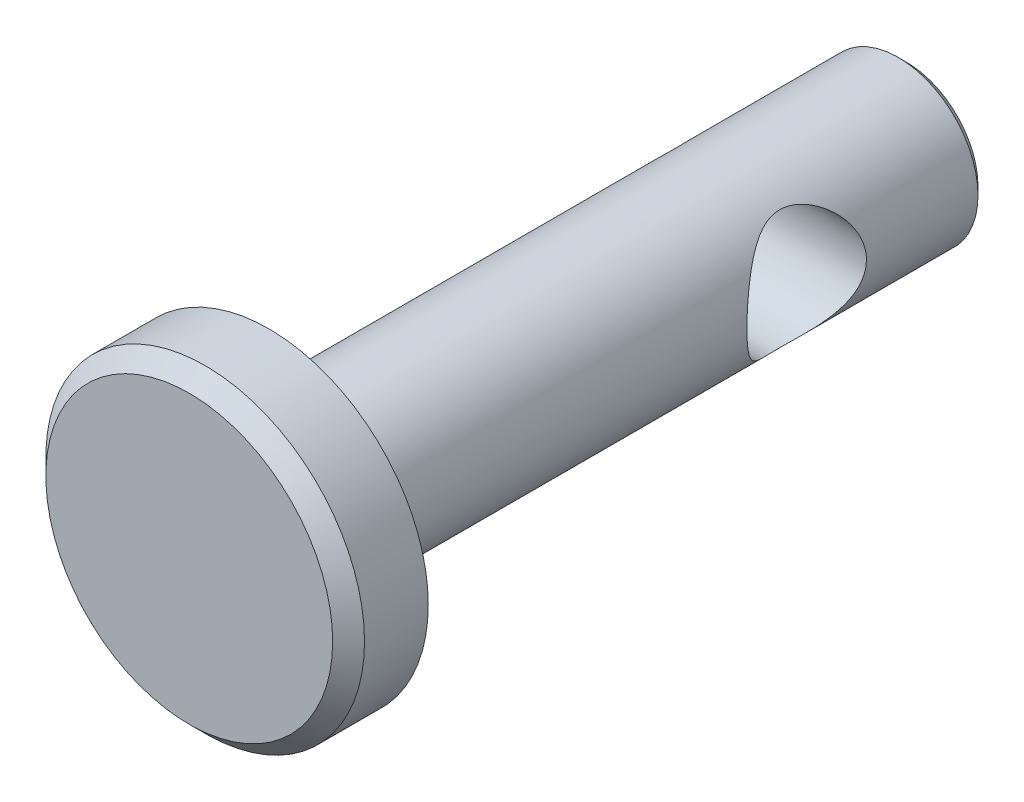
SolidWorks part; units mm, degrees
ref_plane "Front" through (0, 0, 0) normal (0, 0, 1) x (1, 0, 0)
ref_plane "Top" through (0, 0, 0) normal (0, 1, 0) x (1, 0, 0)
ref_plane "Right" through (0, 0, 0) normal (1, 0, 0) x (0, 0, -1)
sketch "Sketch1" plane through (0, 0, 0) normal (0, 0, 1) x (1, 0, 0)
  circle A0 centre (0, 0) radius 1.5875
  point P3 (0, 1.5875)
  point P4 (0, -1.5875)
  dimension "dia" = 3.175
extrude "Extrude1" add sketch "Sketch1" along normal mid plane 12.7
sketch "Sketch2" plane through (0, 0, 6.35) normal (0, 0, 1) x (1, 0, 0)
  circle A0 centre (0, 0) radius 3.175
  dimension "head dia" = 6.35
extrude "Extrude2" add sketch "Sketch2" along normal blind 1.5875
chamfer "Chamfer1" distance 0.3175 angle 45 1 edges at (3.175, 0, 7.9375)
sketch "Sketch3" plane through (0, 0, 0) normal (1, 0, 0) x (0, 0, -1)
  line L0 (-6.35, -1.5875) -> (-6.35, 1.5875) construction
  circle A0 centre (2.7781, 0) radius 1.1906
  point P2 (1.5875, 0)
  dimension "hole dia" = 2.3813
  dimension "useable Lg" = 7.9375
extrude "Extrude3" cut sketch "Sketch3" against normal through all and the other way through all
chamfer "Chamfer2" distance 0.1588 angle 45 1 edges at (1.5875, 0, -6.35)
ref_plane "Plane1" through (0, 0, -2.7781) normal (0, 0, 1) x (1, 0, 0)
sketch "Sketch8" plane through (0, 0, 0) normal (1, 0, 0) x (0, 0, -1)
  line L0 (-7.9375, 2.8575) -> (-7.9375, -2.8575) construction
  line L1 (-7.62, -3.175) -> (-6.35, -3.175) construction
  line L2 (6.35, -1.4288) -> (6.35, 1.4288) construction
  point P0 (-7.9375, 3.175)
  point P1 (-6.35, 3.175)
  point P5 (6.35, 1.5875)
  point P8 (-7.9375, -3.175)
  point P9 (6.35, -1.5875)
equation "\"D1@Chamfer1\" = \"head ht@Extrude2\" * .2"
equation "\"D1@Chamfer2\" = \"dia@Sketch1\" * .05"
